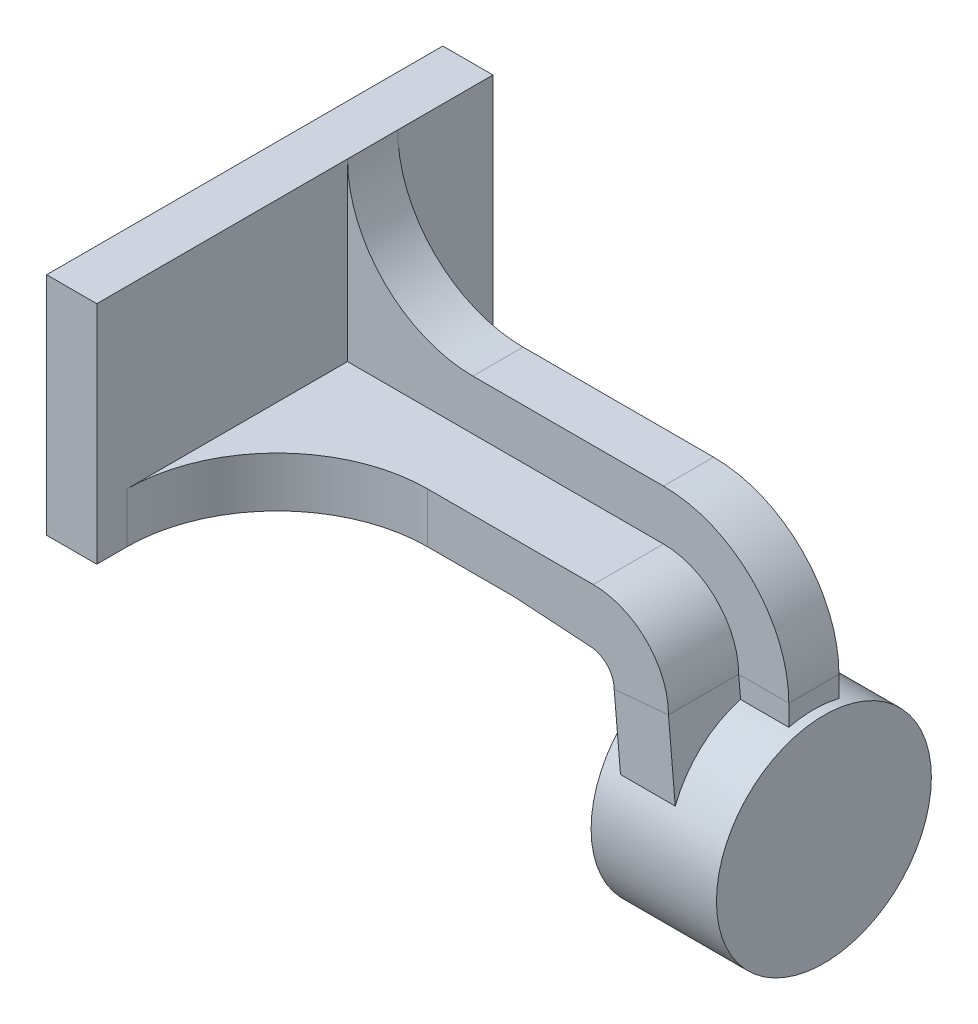
SolidWorks part; units mm, degrees
ref_plane "Ön Düzlem" through (0, 0, 0) normal (0, 0, 1) x (1, 0, 0)
ref_plane "Üst Düzlem" through (0, 0, 0) normal (0, 1, 0) x (1, 0, 0)
ref_plane "Sağ Düzlem" through (0, 0, 0) normal (1, 0, 0) x (0, 0, -1)
sketch "Sketch1" plane through (0, 0, 0) normal (1, 0, 0) x (0, 0, -1)
  line L1 (-80.1113, 40.072) -> (-1.1113, 40.072)
  line L2 (-80.1113, 40.072) -> (-80.1113, -4.928)
  line L3 (-80.1113, -4.928) -> (-1.1113, -4.928)
  line L4 (-1.1113, 40.072) -> (-1.1113, -4.928)
extrude "Boss-Extrude1" add sketch "Sketch1" along normal blind 10
sketch "Sketch2" plane through (10, 0, 0) normal (1, 0, 0) x (0, 0, -1)
  line L0 (-1.1113, 40.072) -> (-30.1113, 40.072)
  line L2 (-1.1113, 40.072) -> (-80.1113, 40.072) construction
  line L3 (-30.1113, 40.072) -> (-30.1113, 5.072)
ref_plane "Plane1" through (0, 0, 30.1113) normal (0, 0, 1) x (1, 0, 0)
sketch "Sketch3" plane through (0, 0, 30.1113) normal (0, 0, 1) x (1, 0, 0)
  line L0 (10, 40.072) -> (10, 15.072)
  line L1 (35, 15.072) -> (73, 15.072)
  line L3 (98, -9.928) -> (88, -9.928)
  line L5 (73, 5.072) -> (10, 5.072)
  line L6 (10, 5.072) -> (10, 40.072)
  arc A0 (10, 40.072) -> (35, 15.072) centre (35, 40.072) ccw
  arc A1 (98, -9.928) -> (73, 15.072) centre (73, -9.928) ccw
  arc A2 (88, -9.928) -> (73, 5.072) centre (73, -9.928) ccw
extrude "Boss-Extrude2" add sketch "Sketch3" against normal blind 10 contours A2 L3 A1 L1 A0 L0 L6 L5
ref_plane "Plane2" through (0, 5.072, 0) normal (0, 1, 0) x (1, 0, 0)
sketch "Sketch5" plane through (0, 5.072, 0) normal (0, 1, 0) x (1, 0, 0)
  line L0 (10, -30.1113) -> (57.3638, -30.1113)
  line L1 (73, -30.1113) -> (10, -30.1113) construction
  line L2 (57.3638, -30.1113) -> (57.3638, -44.1113)
  line L3 (57.3638, -44.1113) -> (40, -44.1113)
  line L4 (10, -30.1113) -> (10, -80.1113) construction
  line L5 (10, -74.1113) -> (10, -80.1113)
  line L6 (10, -30.1113) -> (10, -80.1113)
  arc A0 (10, -74.1113) -> (40, -44.1113) centre (40, -74.1113) cw
  point P13 (10, -44.1113)
  dimension "D1" = 30
extrude "Boss-Extrude11" add sketch "Sketch5" against normal blind 10 separate body contours L6 A0 L3 L2 L0
sketch "Sketch6" plane through (0, 0, 44.1113) normal (0, 0, 1) x (1, 0, 0)
  line L4 (57.3638, 5.072) -> (40, 5.072)
  line L5 (40, 5.072) -> (40, -4.928)
  line L6 (40, -4.928) -> (57.3638, -4.928)
  line L7 (57.3638, -4.928) -> (57.3638, 5.072)
  line L8 (57.3638, 5.072) -> (40, 5.072)
  line L9 (40, 5.072) -> (40, -4.928)
  line L10 (40, -4.928) -> (57.3638, -4.928)
  line L11 (57.3638, -4.928) -> (57.3638, 5.072)
  dimension "D1" = 0
ref_plane "Plane3" through (0, 0, 30.1113) normal (0, 0, 1) x (1, 0, 0)
sketch "Sketch7" plane through (0, 0, 30.1113) normal (0, 0, 1) x (1, 0, 0)
  line L0 (57.3638, 5.072) -> (73, 5.072)
  line L1 (57.3638, -4.928) -> (72.1725, -5.8976)
  line L2 (88, -9.928) -> (77.1725, -10.8976)
  line L3 (57.3638, 5.072) -> (57.3638, -4.928)
  arc A0 (88, -9.928) -> (73, 5.072) centre (73, -9.928) ccw
  arc A1 (77.1725, -10.8976) -> (72.1725, -5.8976) centre (72.1725, -10.8976) ccw
extrude "Boss-Extrude12" add sketch "Sketch7" along normal blind 14
ref_plane "Plane4" through (98, 0, 0) normal (1, 0, 0) x (0, 0, -1)
sketch "Sketch8" plane through (98, 0, 0) normal (1, 0, 0) x (0, 0, -1)
  circle A0 centre (-25.1113, -34.928) radius 16
  dimension "D1" = 75
extrude "Boss-Extrude15" add sketch "Sketch8" against normal blind 23 separate body
sketch "Sketch11" plane through (98, 0, 0) normal (1, 0, 0) x (0, 0, -1)
  circle A0 centre (-25.1113, -34.928) radius 16
extrude "Boss-Extrude16" add sketch "Sketch11" along normal blind 2
sketch "Sketch14" plane through (0, -9.928, 0) normal (0, -1, 0) x (1, 0, 0)
  line L0 (88, 30.1113) -> (98, 30.1113)
  line L1 (98, 30.1113) -> (98, 20.1113)
  line L2 (98, 20.1113) -> (88, 20.1113)
  line L3 (88, 20.1113) -> (88, 30.1113)
extrude "Boss-Extrude20" add sketch "Sketch14" along normal blind 11 separate body
sketch "Sketch15" plane through (1.5822, -17.6672, 0) normal (0.0892, -0.996, 0) x (0.996, 0.0892, 0)
  line L1 (75.8928, 44.1113) -> (86.7637, 44.1113)
  line L2 (75.8928, 44.1113) -> (75.8928, 30.1113)
  line L3 (75.8928, 30.1113) -> (86.7637, 30.1113)
  line L4 (86.7637, 44.1113) -> (86.7637, 30.1113)
extrude "Boss-Extrude21" add sketch "Sketch15" along normal blind 29 separate body
sketch "Sketch16" plane through (100, 0, 0) normal (1, 0, 0) x (0, 0, -1)
  circle A0 centre (-25.1113, -34.928) radius 21.428
extrude "Boss-Extrude22" add sketch "Sketch16" against normal blind 25
ref_plane "Plane5" through (0, 0, 25.1113) normal (0, 0, 1) x (1, 0, 0)
